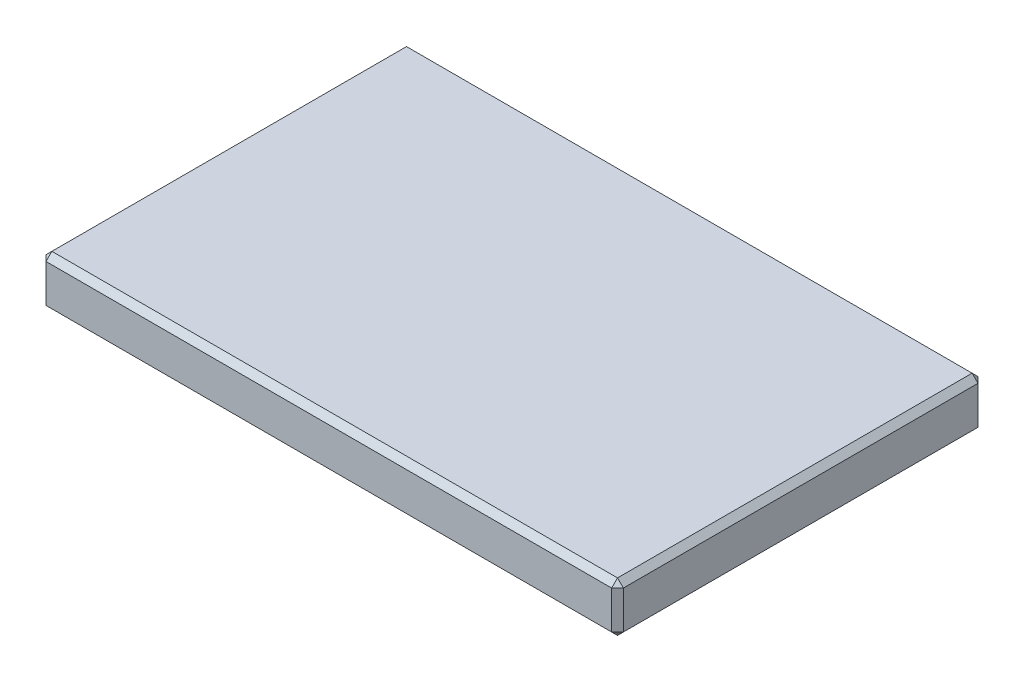
SolidWorks part; units mm, degrees
ref_plane "Piano frontale" through (0, 0, 0) normal (0, 0, 1) x (1, 0, 0)
ref_plane "Piano superiore" through (0, 0, 0) normal (0, 1, 0) x (1, 0, 0)
ref_plane "Piano destro" through (0, 0, 0) normal (1, 0, 0) x (0, 0, -1)
sketch "Schizzo1" plane through (0, 0, 0) normal (0, 1, 0) x (1, 0, 0)
  line L1 (-98.5, -62.5) -> (98.5, -62.5)
  line L2 (-98.5, -62.5) -> (-98.5, 62.5)
  line L3 (-98.5, 62.5) -> (98.5, 62.5)
  line L4 (98.5, -62.5) -> (98.5, 62.5)
  line L5 (-98.5, -62.5) -> (98.5, 62.5) construction
  line L6 (-98.5, 62.5) -> (98.5, -62.5) construction
  point P0 (0, 0)
  dimension "D1" = 197
  dimension "D2" = 125
extrude "Estrusione-Estrusione1" add sketch "Schizzo1" along normal blind 17
chamfer "Smusso1" distance 2 angle 45 12 edges at (98.5, 8.5, -62.5) (-98.5, 8.5, -62.5) (-98.5, 8.5, 62.5) (0, 17, 62.5) (-98.5, 17, 0) (0, 17, -62.5) (98.5, 17, 0) (98.5, 8.5, 62.5) (0, 0, 62.5) (-98.5, 0, 0) (0, 0, -62.5) (98.5, 0, 0)
